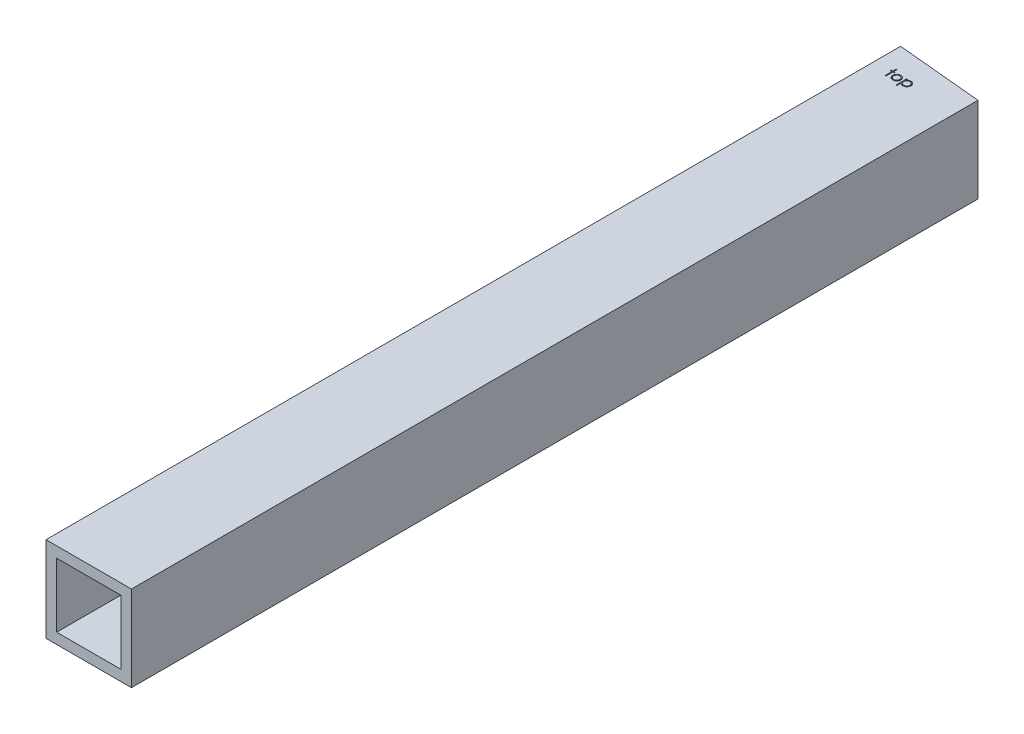
SolidWorks part; units mm, degrees
ref_plane "Front Plane" through (0, 0, 0) normal (0, 0, 1) x (1, 0, 0)
ref_plane "Top Plane" through (0, 0, 0) normal (0, 1, 0) x (1, 0, 0)
ref_plane "Right Plane" through (0, 0, 0) normal (1, 0, 0) x (0, 0, -1)
sketch "Sketch2" plane through (0, 0, 0) normal (0, 0, 1) x (1, 0, 0)
  line L1 (0, 0) -> (25.4, 0)
  line L2 (0, 0) -> (0, 25.4)
  line L3 (0, 25.4) -> (25.4, 25.4)
  line L4 (25.4, 0) -> (25.4, 25.4)
  line L5 (3.175, 22.225) -> (22.225, 22.225)
  line L6 (3.175, 22.225) -> (3.175, 3.175)
  line L7 (3.175, 3.175) -> (22.225, 3.175)
  line L8 (22.225, 22.225) -> (22.225, 3.175)
  dimension "D1" = 25.4
  dimension "D2" = 25.4
  dimension "D3" = 3.175
  dimension "D4" = 3.175
  dimension "D5" = 3.175
  dimension "D6" = 3.175
extrude "Boss-Extrude1" add sketch "Sketch2" along normal blind 254
sketch "Sketch3" plane through (0, 25.4, 0) normal (0, 1, 0) x (1, 0, 0)
  line L0 (0, 0) -> (25.4, -2.392)
  line L1 (25.4, -254) -> (25.4, 0) construction
  line L2 (25.4, -2.392) -> (25.4, 0)
  line L3 (25.4, 0) -> (0, 0)
  text T0 "top\r\n"
  dimension "D1" = 84.62
extrude "Cut-Extrude1" cut sketch "Sketch3" against normal through all
